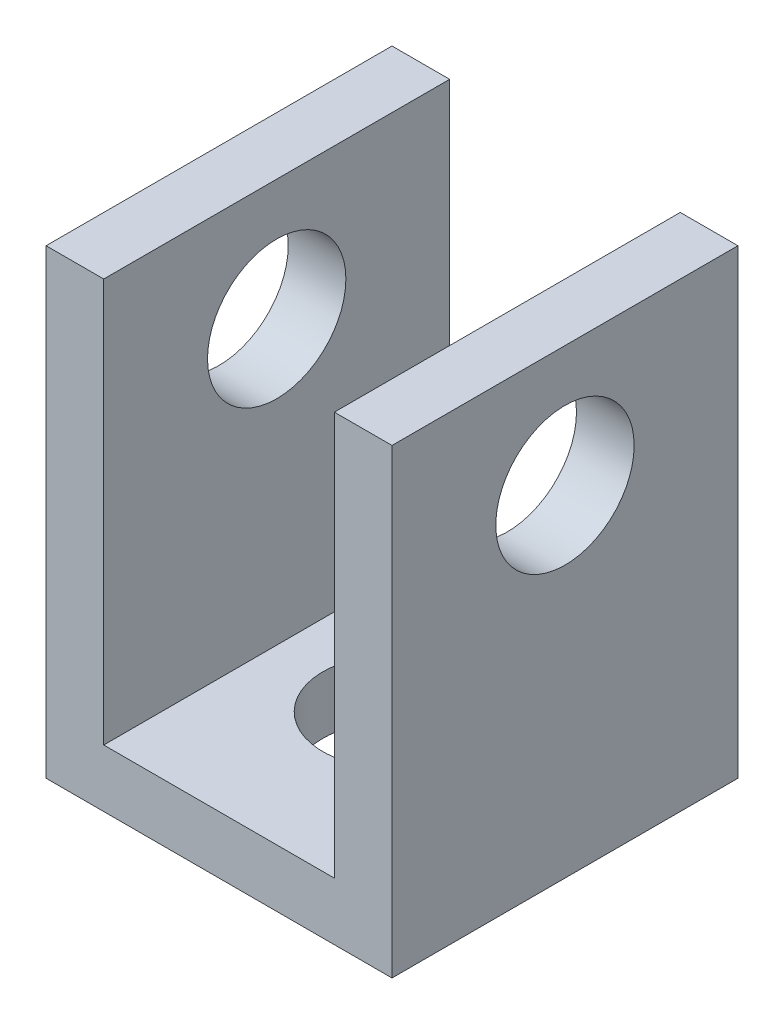
SolidWorks part; units mm, degrees
ref_plane "Front Plane" through (0, 0, 0) normal (0, 0, 1) x (1, 0, 0)
ref_plane "Top Plane" through (0, 0, 0) normal (0, 1, 0) x (1, 0, 0)
ref_plane "Right Plane" through (0, 0, 0) normal (1, 0, 0) x (0, 0, -1)
sketch "Sketch1" plane through (0, 0, 0) normal (0, 0, 1) x (1, 0, 0)
  line L0 (-30.1753, 12.3519) -> (-30.1753, -7.6481)
  line L1 (-30.1753, -7.6481) -> (-15.1753, -7.6481)
  line L2 (-15.1753, -7.6481) -> (-15.1753, 12.3519)
  line L3 (-27.6753, 12.3519) -> (-27.6753, -5.1481)
  line L4 (-27.6753, -5.1481) -> (-17.6753, -5.1481)
  line L5 (-17.6753, -5.1481) -> (-17.6753, 12.3519)
  line L6 (-30.1753, 12.3519) -> (-27.6753, 12.3519)
  line L7 (-17.6753, 12.3519) -> (-15.1753, 12.3519)
  dimension "D1" = 20
  dimension "D2" = 15
  dimension "D3" = 20
  dimension "D4" = 2.5
extrude "Boss-Extrude1" add sketch "Sketch1" along normal blind 15
sketch "Sketch2" plane through (-15.1753, 0, 0) normal (1, 0, 0) x (0, 0, -1)
  circle A0 centre (-7.5, 7.1041) radius 3
extrude "Cut-Extrude1" cut sketch "Sketch2" against normal blind 17
sketch "Sketch3" plane through (0, -7.6481, 0) normal (0, -1, 0) x (-1, 0, 0)
  circle A0 centre (22.6753, -7.5) radius 3
extrude "Cut-Extrude2" cut sketch "Sketch3" against normal blind 17
